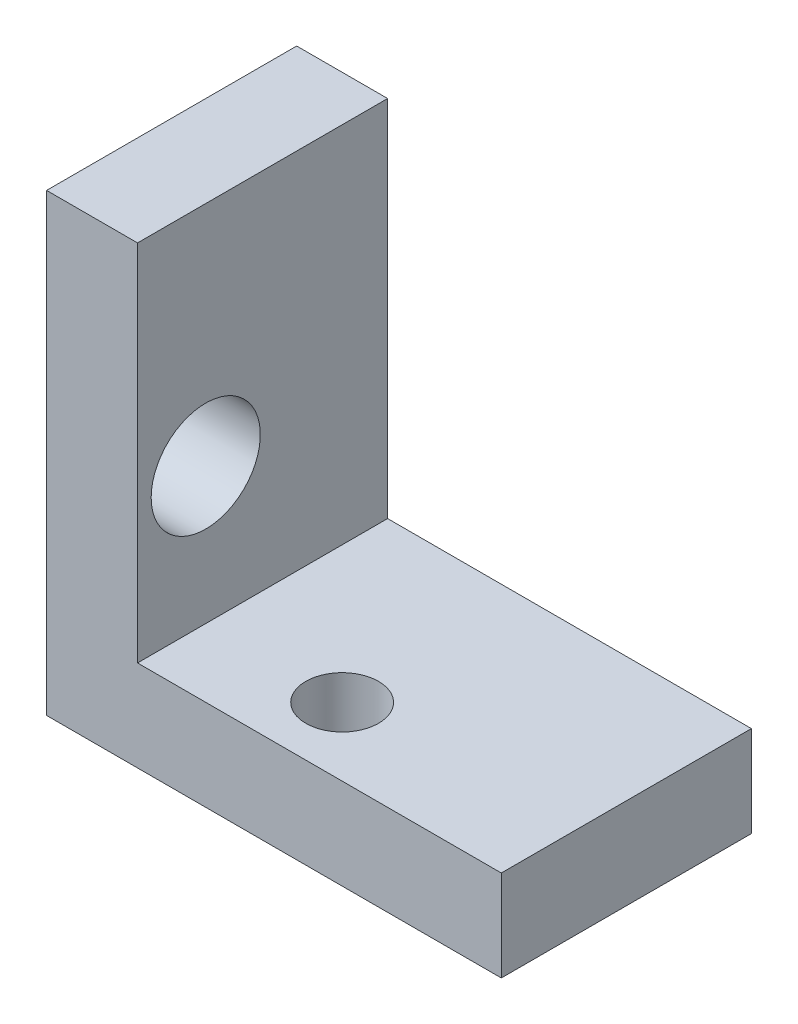
SolidWorks part; units mm, degrees
material "6061-T6 (SS)"
ref_plane "Front Plane" through (0, 0, 0) normal (0, 0, 1) x (1, 0, 0)
ref_plane "Top Plane" through (0, 0, 0) normal (0, 1, 0) x (1, 0, 0)
ref_plane "Right Plane" through (0, 0, 0) normal (1, 0, 0) x (0, 0, -1)
sketch "Sketch1" plane through (0, 0, 0) normal (0, 0, 1) x (1, 0, 0)
  line L0 (0, 0) -> (0, 10)
  line L1 (0, 10) -> (2, 10)
  line L2 (2, 10) -> (2, 2)
  line L3 (2, 2) -> (10, 2)
  line L4 (10, 2) -> (10, 0)
  line L5 (10, 0) -> (0, 0)
  dimension "D1" = 2
  dimension "D2" = 10
extrude "Boss-Extrude1" add sketch "Sketch1" along normal blind 5.5
hole_wizard "M2 Clearance Hole1" positions "Sketch2" profile "Sketch3" hole size "M2" standard "ANSI Metric" end condition up to next
sketch "Sketch2" plane through (0, 0, 0) normal (-1, 0, 0) x (0, 0, 1)
  line L0 (0, 10) -> (0, 0) construction
  line L1 (5.5, 10) -> (0, 10) construction
  point P0 (4, 5)
  dimension "D1" = 4
  dimension "D2" = 5
sketch "Sketch3" plane through (0, 5, 4) normal (0, 1, 0) x (0, 0, 1)
  line L0 (0, 0) -> (0, 2)
  line L1 (0, 2) -> (1.2, 2)
  line L2 (1.2, 2) -> (1.2, 0.025)
  line L3 (1.2, 0.025) -> (1.225, 0)
  line L5 (1.225, 0) -> (0, 0)
  line L6 (-1.2, 0.025) -> (-1.225, 0) construction
  line L11 (0, -6.35) -> (0, 107.95) construction
  dimension "Thru Hole Dia." = 2.4
  dimension "Thru Hole Depth" = 2
  dimension "Near C'Sink Dia." = 2.45
  dimension "Near C'Sink Angle" = 90
hole_wizard "M2x0.4 Tapped Hole1" positions "Sketch4" profile "Sketch5" tap size "M2x0.4" standard "ANSI Metric" end condition up to next
sketch "Sketch4" plane through (0, 0, 0) normal (0, -1, 0) x (-1, 0, 0)
  line L0 (-10, -5.5) -> (-10, 0) construction
  line L1 (0, 0) -> (-10, 0) construction
  point P0 (-5, -4)
  dimension "D1" = 5
  dimension "D2" = 4
sketch "Sketch5" plane through (5, 0, 4) normal (1, 0, 0) x (0, 0, -1)
  line L0 (0, 0) -> (0, 2)
  line L1 (0, 2) -> (0.8, 2)
  line L2 (0.8, 2) -> (0.8, 0.425)
  line L3 (0.8, 0.425) -> (1.225, 0)
  line L5 (1.225, 0) -> (0, 0)
  line L6 (-0.8, 0.425) -> (-1.225, 0) construction
  line L11 (0, -6.35) -> (0, 107.95) construction
  dimension "Thru Tap Drill Dia." = 1.6
  dimension "Thru Tap Drill Depth" = 2
  dimension "Near C'Sink Dia." = 2.45
  dimension "Near C'Sink Angle" = 90
cosmetic thread "Hole Thread1"
